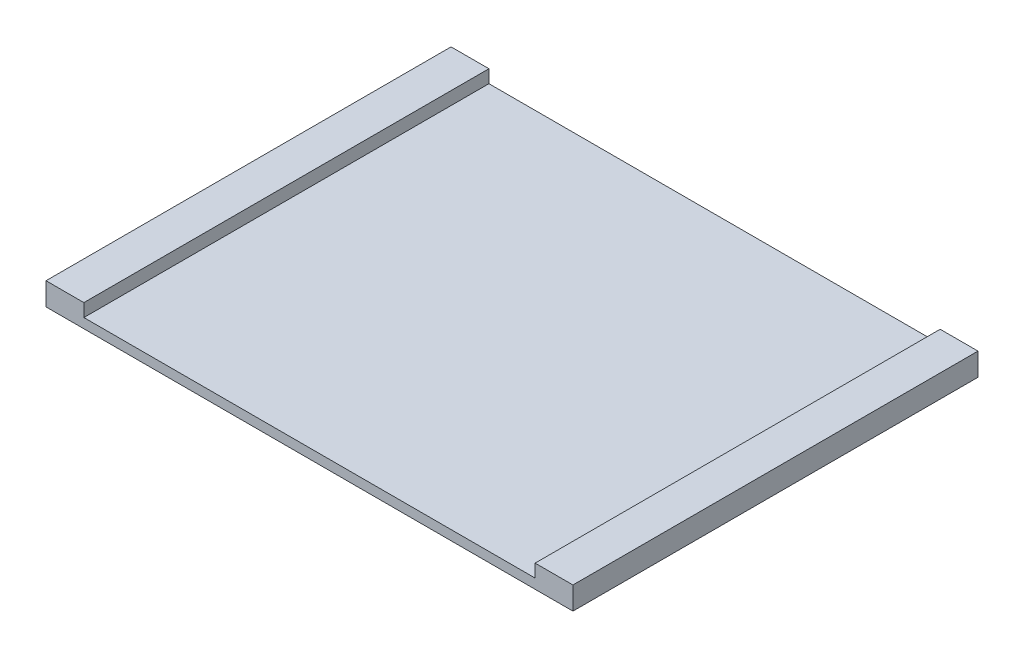
SolidWorks part; units mm, degrees
ref_plane "Plan de face" through (0, 0, 0) normal (0, 0, 1) x (1, 0, 0)
ref_plane "Plan de dessus" through (0, 0, 0) normal (0, 1, 0) x (1, 0, 0)
ref_plane "Plan de droite" through (0, 0, 0) normal (1, 0, 0) x (0, 0, -1)
sketch "Esquisse8" plane through (0, 0, 0) normal (0, 1, 0) x (1, 0, 0)
  line L1 (0, 0) -> (69.596, 0)
  line L2 (0, 0) -> (0, 50.8)
  line L3 (0, 50.8) -> (69.596, 50.8)
  line L4 (69.596, 0) -> (69.596, 50.8)
  point P5 (76.4156, 46.0335)
extrude "Boss.-Extru.2" add sketch "Esquisse8" along normal blind 4
sketch "Esquisse9" plane through (0, 4, 0) normal (0, 1, 0) x (1, 0, 0)
  line L1 (-5.842, 56.638) -> (75.438, 56.638)
  line L2 (-5.842, 56.638) -> (-5.842, -5.842)
  line L3 (-5.842, -5.842) -> (75.438, -5.842)
  line L4 (75.438, 56.638) -> (75.438, -5.842)
  point P4 (0, 0)
  point P5 (0, 0)
  point P6 (0, 0)
extrude "Boss.-Extru.3" add sketch "Esquisse9" along normal blind 1.5
sketch "Esquisse10" plane through (0, 4, 0) normal (0, -1, 0) x (1, 0, 0)
  line L0 (75.438, -56.638) -> (-5.842, -56.638) construction
  line L1 (-5.842, 5.842) -> (0, 5.842)
  line L2 (-5.842, 5.842) -> (-5.842, -56.638)
  line L3 (-5.842, -56.638) -> (0, -56.638)
  line L4 (0, 5.842) -> (0, -56.638)
extrude "Boss.-Extru.4" add sketch "Esquisse10" against normal blind 3.5
sketch "Esquisse11" plane through (0, 4, 0) normal (0, -1, 0) x (-1, 0, 0)
  line L0 (-75.438, 56.638) -> (5.842, 56.638) construction
  line L1 (-75.438, -5.842) -> (-69.6036, -5.842)
  line L2 (-75.438, -5.842) -> (-75.438, 56.638)
  line L3 (-75.438, 56.638) -> (-69.6036, 56.638)
  line L4 (-69.6036, -5.842) -> (-69.6036, 56.638)
extrude "Boss.-Extru.5" add sketch "Esquisse11" against normal blind 3.5
